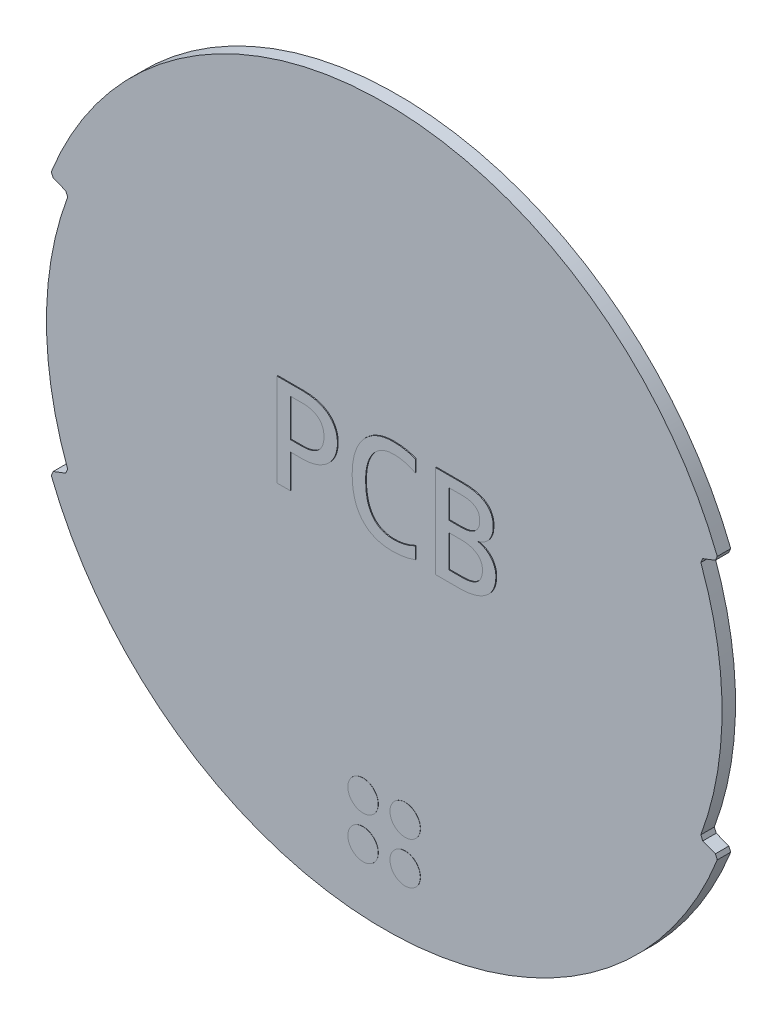
SolidWorks part; units mm, degrees
material "A-玻璃纤维"
ref_plane "前视基准面" through (0, 0, 0) normal (0, 0, 1) x (1, 0, 0)
ref_plane "上视基准面" through (0, 0, 0) normal (0, 1, 0) x (1, 0, 0)
ref_plane "右视基准面" through (0, 0, 0) normal (1, 0, 0) x (0, 0, -1)
sketch "草图1" plane through (0, 0, 0) normal (0, 0, 1) x (1, 0, 0)
  line L0 (18.284, -6.7782) -> (18.3633, 6.5603) construction
  line L1 (-18.284, 6.7782) -> (-18.3633, -6.5603) construction
  line L2 (18.284, -6.7782) -> (18.3633, 6.5603) construction
  line L3 (-18.284, 6.7782) -> (-18.3633, -6.5603) construction
  line L4 (2.55, -18.945) -> (-2.55, -18.945) construction
  line L5 (2.7, -13.695) -> (2.7, -18.795) construction
  line L6 (-2.55, -13.545) -> (2.55, -13.545) construction
  line L7 (-2.7, -18.795) -> (-2.7, -13.695) construction
  line L8 (2.55, -18.945) -> (-2.55, -18.945) construction
  line L9 (2.7, -13.695) -> (2.7, -18.795) construction
  line L10 (-2.55, -13.545) -> (2.55, -13.545) construction
  line L11 (-2.7, -18.795) -> (-2.7, -13.695) construction
  arc A0 (7.3321, -19.945) -> (-7.3321, -19.945) centre (0, 0) ccw
  arc A1 (7.3321, -19.945) -> (-7.3321, -19.945) centre (0, 0) cw
  arc A13 (18.3633, 6.5603) -> (-18.284, 6.7782) centre (0, 0) ccw construction
  arc A14 (-18.3633, -6.5603) -> (18.284, -6.7782) centre (0, 0) ccw construction
  arc A15 (18.3633, 6.5603) -> (-18.284, 6.7782) centre (0, 0) ccw construction
  arc A16 (-18.3633, -6.5603) -> (18.284, -6.7782) centre (0, 0) ccw construction
  arc A17 (-2.7, -18.795) -> (-2.55, -18.945) centre (-2.55, -18.795) ccw construction
  arc A18 (2.55, -18.945) -> (2.7, -18.795) centre (2.55, -18.795) ccw construction
  arc A19 (2.7, -13.695) -> (2.55, -13.545) centre (2.55, -13.695) ccw construction
  arc A20 (-2.55, -13.545) -> (-2.7, -13.695) centre (-2.55, -13.695) ccw construction
  arc A21 (-2.7, -18.795) -> (-2.55, -18.945) centre (-2.55, -18.795) ccw construction
  arc A22 (2.55, -18.945) -> (2.7, -18.795) centre (2.55, -18.795) ccw construction
  arc A23 (2.7, -13.695) -> (2.55, -13.545) centre (2.55, -13.695) ccw construction
  arc A24 (-2.55, -13.545) -> (-2.7, -13.695) centre (-2.55, -13.695) ccw construction
  point P3 (0, -19.945)
  dimension "D1" = 42.5
extrude "凸台-拉伸1" add sketch "草图1" along normal blind 0.8
sketch "草图3" plane through (0, 0, 0) normal (0, 0, -1) x (-1, 0, 0)
  line L0 (0, -16.245) -> (0, 0.0046) construction
  line L3 (-2.7, -13.545) -> (2.7, -13.545) construction
  line L4 (-2.7, -13.545) -> (-2.7, -18.945) construction
  line L5 (-2.7, -18.945) -> (2.7, -18.945) construction
  line L6 (2.7, -13.545) -> (2.7, -18.945) construction
  line L7 (-2.7, -13.545) -> (2.7, -18.945) construction
  line L8 (-2.7, -18.945) -> (2.7, -13.545) construction
  line L9 (-2.7, -16.245) -> (2.7, -16.245) construction
  circle A0 centre (-1.25, -14.995) radius 0.9
  circle A3 centre (1.25, -14.995) radius 0.9
  circle A4 centre (1.25, -17.495) radius 0.9
  circle A5 centre (-1.25, -17.495) radius 0.9
  point P0 (0, -16.245)
  dimension "D6" = 1.8
  dimension "D2" = 5.4
  dimension "D3" = 5.4
  dimension "D5" = 2.5
sketch "草图4" plane through (0, 0, 0.8) normal (0, 0, 1) x (1, 0, 0)
  text T0 "PCB" font "Consolas" height 5.5
  point P1 (-6.3763, -0.2119)
  point P2 (-6.78, -1.6906)
  point P3 (-5.981, -2.1536)
  point P4 (0, 0)
  point P5 (-6.7658, -1.9177)
  point P6 (0, 0)
  point P7 (0, 0)
  point P8 (0, 0)
  point P9 (-7.161, -1.3797)
  point P10 (0, 0)
  point P11 (0, 0)
  point P12 (0, 0)
  point P13 (0, 0)
  point P14 (-6.9562, -1.4444)
extrude "凸台-拉伸2" add sketch "草图4" along normal blind 0.05 and the other way blind 0.85 separate body
extrude "凸台-拉伸3" add sketch "草图3" along normal blind 0.01 and the other way blind 0.81 separate body
sketch "草图5" plane through (0, 0, 0.8) normal (0, 0, 1) x (1, 0, 0)
  line L0 (0, 0) -> (50000, 0) construction
  line L1 (0, 0) -> (19.8386, 7.6153) construction
  line L2 (19.8386, 7.6153) -> (18.7183, 7.1853)
  line L3 (0, 0) -> (19.8386, -7.6153) construction
  line L4 (19.8386, -7.6153) -> (18.7183, -7.1853)
  line L5 (0, 0.9042) -> (0, -49999.0958) construction
  line L6 (-19.8386, -7.6153) -> (-18.7183, -7.1853)
  line L7 (-19.8386, 7.6153) -> (-18.7183, 7.1853)
  arc A0 (19.8386, 7.6153) -> (19.8386, -7.6153) centre (0, 0) cw
  circle A1 centre (0, 0) radius 21.25 construction
  arc A2 (18.7183, 7.1853) -> (18.7183, -7.1853) centre (0, 0) cw
  arc A3 (-18.7183, 7.1853) -> (-18.7183, -7.1853) centre (0, 0) ccw
  arc A4 (-19.8386, 7.6153) -> (-19.8386, -7.6153) centre (0, 0) ccw
  dimension "D1" = 21
  dimension "D2" = 1.2
extrude "切除-拉伸3" cut sketch "草图5" against normal through all
chamfer "倒角2" distance 0.2 angle 45 8 edges at (18.7183, -7.1853, 0.4) (19.8386, -7.6153, 0.4) (19.8386, 7.6153, 0.4) (18.7183, 7.1853, 0.4) (-19.8386, 7.6153, 0.4) (-18.7183, 7.1853, 0.4) (-19.8386, -7.6153, 0.4) (-18.7183, -7.1853, 0.4)
